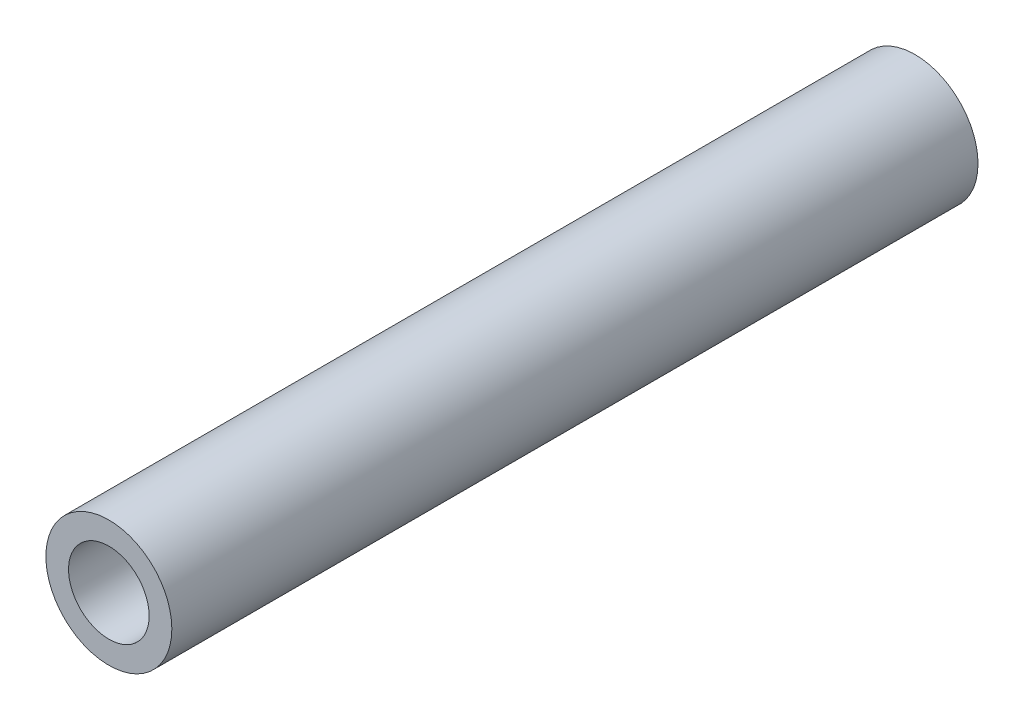
SolidWorks part; units mm, degrees
material "6061-T6 (SS)"
ref_plane "Front" through (0, 0, 0) normal (0, 0, 1) x (1, 0, 0)
ref_plane "Top" through (0, 0, 0) normal (0, 1, 0) x (1, 0, 0)
ref_plane "Right" through (0, 0, 0) normal (1, 0, 0) x (0, 0, -1)
sketch "Sketch1" plane through (0, 0, 0) normal (0, 0, 1) x (1, 0, 0)
  circle A0 centre (0, 0) radius 3.9688
  circle A1 centre (0, 0) radius 2.54
  dimension "D2" = 5.08
  dimension "D1" = 7.9375
extrude "Boss-Extrude1" add sketch "Sketch1" along normal blind 50.8
